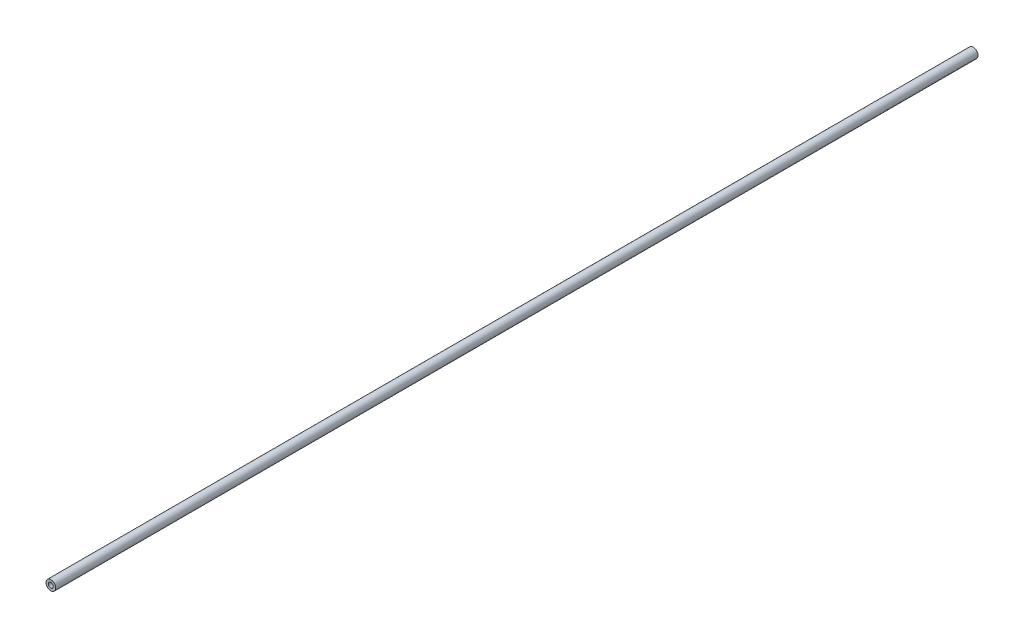
SolidWorks part; units mm, degrees
material "PTFE (general)"
ref_plane "Front Plane" through (0, 0, 0) normal (0, 0, 1) x (1, 0, 0)
ref_plane "Top Plane" through (0, 0, 0) normal (0, 1, 0) x (1, 0, 0)
ref_plane "Right Plane" through (0, 0, 0) normal (1, 0, 0) x (0, 0, -1)
sketch "Sketch1" plane through (0, 0, 0) normal (0, 0, 1) x (1, 0, 0)
  circle A0 centre (0, 0) radius 2
  circle A1 centre (0, 0) radius 1
  dimension "D1" = 4
  dimension "D2" = 2
extrude "Boss-Extrude1" add sketch "Sketch1" along normal blind 380
